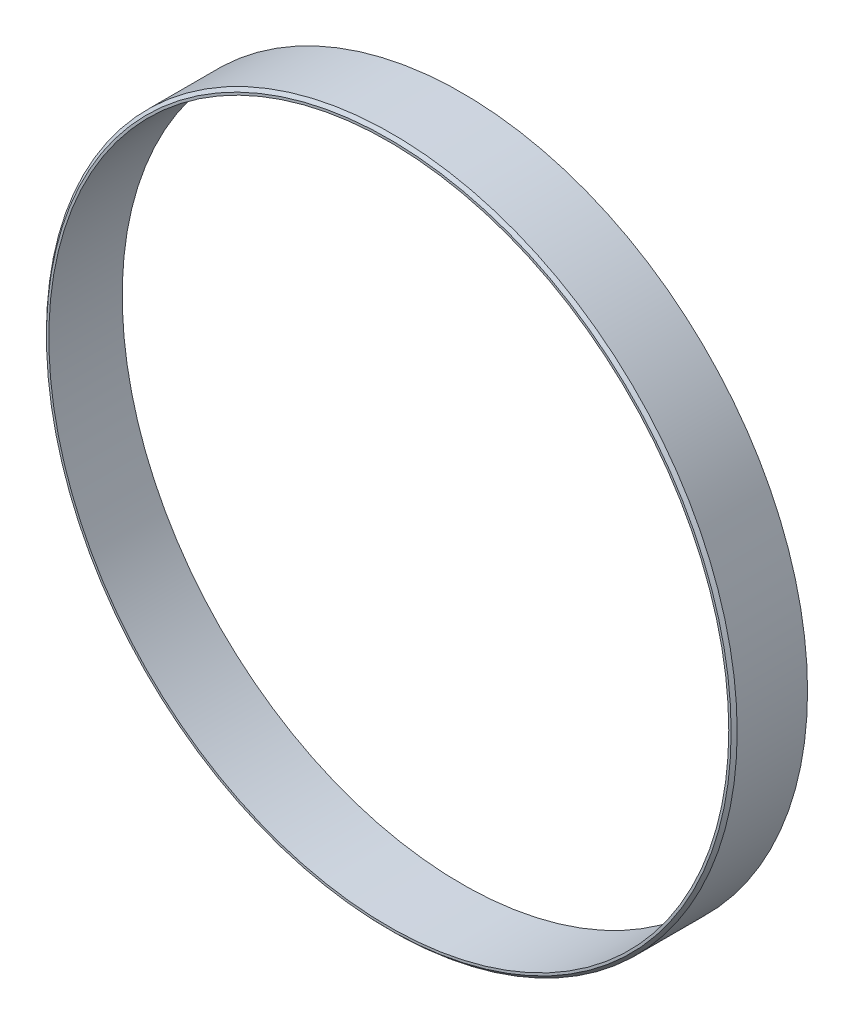
SolidWorks part; units mm, degrees
ref_plane "Piano frontale" through (0, 0, 0) normal (0, 0, 1) x (1, 0, 0)
ref_plane "Piano superiore" through (0, 0, 0) normal (0, 1, 0) x (1, 0, 0)
ref_plane "Piano destro" through (0, 0, 0) normal (1, 0, 0) x (0, 0, -1)
sketch "Schizzo1" plane through (0, 0, 0) normal (0, 0, 1) x (1, 0, 0)
  circle A0 centre (0, 0) radius 78.75
  circle A1 centre (0, 0) radius 80
  dimension "D1" = 157.5
  dimension "D2" = 160
extrude "Estrusione-Estrusione1" add sketch "Schizzo1" along normal blind 17
chamfer "Smusso1" distance 0.7 angle 45 1 edges at (80, 0, 17)
